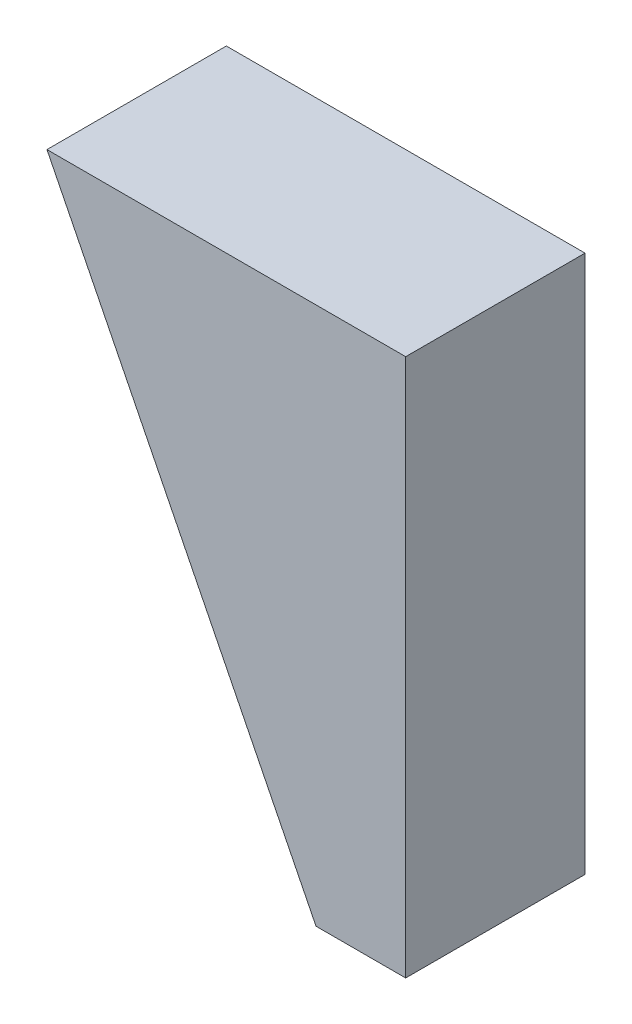
SolidWorks part; units mm, degrees
material "Pine"
ref_plane "Front Plane" through (0, 0, 0) normal (0, 0, 1) x (1, 0, 0)
ref_plane "Top Plane" through (0, 0, 0) normal (0, 1, 0) x (1, 0, 0)
ref_plane "Right Plane" through (0, 0, 0) normal (1, 0, 0) x (0, 0, -1)
sketch "Sketch1" plane through (0, 0, 0) normal (0, 0, 1) x (1, 0, 0)
  line L0 (1341.25, 19.05) -> (1341.25, -133.35)
  line L1 (2286, 19.05) -> (0, 19.05) construction
  line L2 (1315.85, -133.35) -> (1239.65, 19.05)
  line L3 (1239.65, 19.05) -> (1341.25, 19.05)
  line L4 (1341.25, -146.55) -> (1341.25, -2021.55) construction
  line L5 (1341.25, -133.35) -> (1315.85, -133.35)
  dimension "D1" = 101.6
  dimension "D2" = 152.4
  dimension "D3" = 25.4
extrude "Boss-Extrude1" add sketch "Sketch1" along normal blind 50.8
